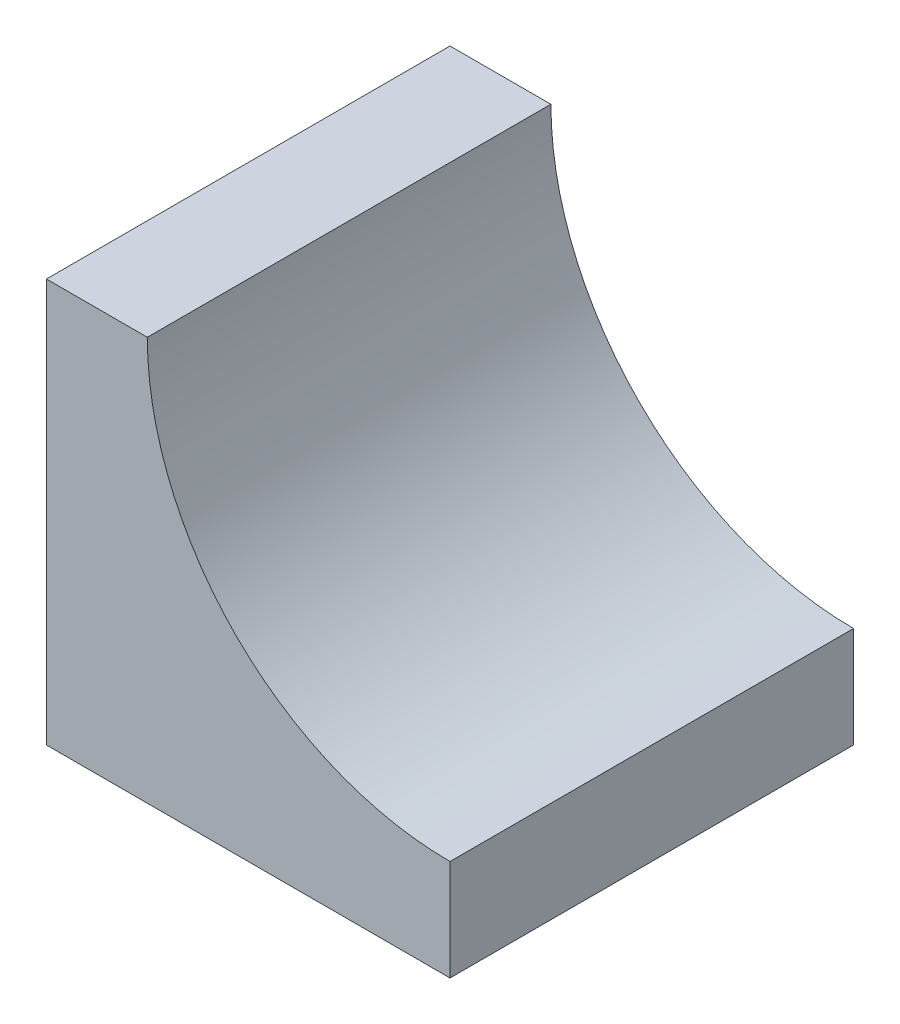
SolidWorks part; units mm, degrees
ref_plane "Front Plane" through (0, 0, 0) normal (0, 0, 1) x (1, 0, 0)
ref_plane "Top Plane" through (0, 0, 0) normal (0, 1, 0) x (1, 0, 0)
ref_plane "Right Plane" through (0, 0, 0) normal (1, 0, 0) x (0, 0, -1)
sketch "Sketch1" plane through (0, 0, 0) normal (0, 0, 1) x (1, 0, 0)
  line L0 (20, 5) -> (20, 0)
  line L1 (0, 0) -> (20, 0)
  line L2 (0, 0) -> (0, 20)
  line L3 (0, 20) -> (5, 20)
  arc A0 (5, 20) -> (20, 5) centre (20, 20) ccw
  dimension "D1" = 5
  dimension "D2" = 20
  dimension "D3" = 20
  dimension "D4" = 5
extrude "Boss-Extrude1" add sketch "Sketch1" along normal blind 20
